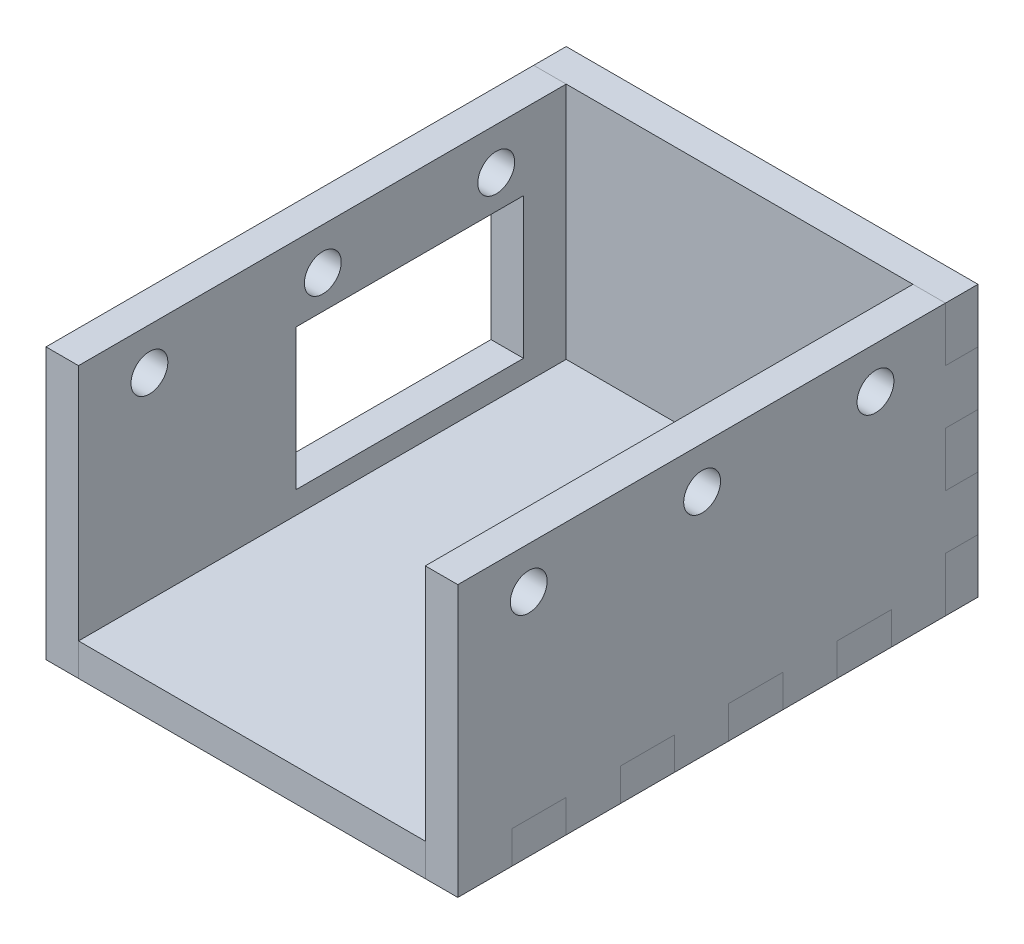
SolidWorks part; units mm, degrees
ref_plane "Front Plane" through (0, 0, 0) normal (0, 0, 1) x (1, 0, 0)
ref_plane "Top Plane" through (0, 0, 0) normal (0, 1, 0) x (1, 0, 0)
ref_plane "Right Plane" through (0, 0, 0) normal (1, 0, 0) x (0, 0, -1)
sketch "Sketch1" plane through (0, 0, 0) normal (0, 1, 0) x (1, 0, 0)
  line L33 (0, 0) -> (5, 0)
  line L34 (5, 0) -> (5, 3)
  line L54 (5, 3) -> (10, 3)
  line L55 (10, 3) -> (10, 0)
  line L56 (10, 0) -> (15, 0)
  line L57 (15, 0) -> (15, 3)
  line L58 (15, 3) -> (20, 3)
  line L59 (20, 3) -> (20, 0)
  line L60 (20, 0) -> (25, 0)
  line L61 (25, 0) -> (25, 3)
  line L62 (25, 3) -> (30, 3)
  line L63 (30, 3) -> (30, 0)
  line L64 (30, 0) -> (32, 0)
  line L65 (32, 0) -> (32, -5)
  line L66 (32, -5) -> (35, -5)
  line L67 (35, -5) -> (35, -10)
  line L68 (35, -10) -> (32, -10)
  line L69 (32, -10) -> (32, -15)
  line L70 (32, -15) -> (35, -15)
  line L71 (35, -15) -> (35, -20)
  line L72 (35, -20) -> (32, -20)
  line L73 (32, -20) -> (32, -25)
  line L74 (32, -25) -> (35, -25)
  line L75 (35, -25) -> (35, -30)
  line L76 (35, -30) -> (32, -30)
  line L77 (32, -30) -> (32, -35)
  line L78 (32, -35) -> (35, -35)
  line L79 (35, -35) -> (35, -40)
  line L80 (35, -40) -> (32, -40)
  line L81 (32, -40) -> (32, -45)
  line L82 (16, -1020.6314) -> (16, 48979.3686) construction
  line L83 (0, -40) -> (0, -45)
  line L84 (-3, -40) -> (0, -40)
  line L85 (-3, -35) -> (-3, -40)
  line L86 (0, -35) -> (-3, -35)
  line L87 (0, -30) -> (0, -35)
  line L88 (-3, -30) -> (0, -30)
  line L89 (-3, -25) -> (-3, -30)
  line L90 (0, -25) -> (-3, -25)
  line L91 (0, -20) -> (0, -25)
  line L92 (-3, -20) -> (0, -20)
  line L93 (-3, -15) -> (-3, -20)
  line L94 (0, -15) -> (-3, -15)
  line L95 (0, -10) -> (0, -15)
  line L96 (-3, -10) -> (0, -10)
  line L97 (-3, -5) -> (-3, -10)
  line L98 (0, -5) -> (-3, -5)
  line L99 (0, 0) -> (0, -5)
  line L100 (2, 0) -> (0, 0)
  line L101 (0, -45) -> (32, -45)
  point P21 (32, -2.5)
  dimension "D1" = 4
  dimension "D2" = 16
extrude "Boss-Extrude1" add sketch "Sketch1" along normal blind 3
sketch "Sketch4" plane through (32, 0, 0) normal (1, 0, 0) x (0, 0, -1)
  line L0 (-5, 3) -> (-5, 0)
  line L1 (-5, 0) -> (0, 0)
  line L2 (0, 0) -> (0, 3)
  line L3 (-5, 3) -> (-10, 3)
  line L4 (-15, 3) -> (-15, 0)
  line L5 (-15, 0) -> (-10, 0)
  line L6 (-10, 0) -> (-10, 3)
  line L7 (-15, 3) -> (-20, 3)
  line L8 (-25, 3) -> (-25, 0)
  line L9 (-25, 0) -> (-20, 0)
  line L10 (-20, 0) -> (-20, 3)
  line L11 (-25, 3) -> (-30, 3)
  line L12 (-35, 3) -> (-35, 0)
  line L13 (-35, 0) -> (-30, 0)
  line L14 (-30, 0) -> (-30, 3)
  line L15 (-35, 3) -> (-40, 3)
  line L16 (-40, 3) -> (-40, 0)
  line L17 (-40, 3) -> (-40, 0) construction
  line L18 (-40, 0) -> (-45, 0)
  line L19 (-45, 0) -> (-45, 3)
  line L20 (-45, 3) -> (-45, 25)
  line L21 (-45, 25) -> (0, 25)
  line L22 (0, 25) -> (0, 20)
  line L23 (0, 20) -> (3, 20)
  line L24 (3, 20) -> (3, 15)
  line L25 (3, 15) -> (0, 15)
  line L26 (0, 15) -> (0, 10)
  line L27 (0, 10) -> (3, 10)
  line L28 (3, 10) -> (3, 5)
  line L29 (3, 5) -> (0, 5)
  line L30 (0, 3) -> (0, 5)
  dimension "D1" = 22
extrude "Boss-Extrude2" add sketch "Sketch4" along normal blind 3 separate body
ref_plane "Plane1" through (16, 0, 0) normal (-1, 0, 0) x (0, 0, 1)
mirror "Mirror1" about plane through (16, 0, 0) normal (-1, 0, 0) of bodies 102
sketch "Sketch5" plane through (0, 0, 0) normal (0, 0, -1) x (-1, 0, 0)
  line L0 (-35, 25) -> (3, 25)
  line L1 (3, 25) -> (3, 20)
  line L2 (3, 20) -> (0, 20)
  line L3 (0, 20) -> (0, 15)
  line L4 (0, 15) -> (3, 15)
  line L5 (3, 15) -> (3, 10)
  line L6 (3, 10) -> (0, 10)
  line L7 (0, 10) -> (0, 5)
  line L8 (0, 5) -> (3, 5)
  line L9 (3, 5) -> (3, 0)
  line L10 (3, 0) -> (0, 0)
  line L11 (-5, 0) -> (-5, 3)
  line L12 (-5, 3) -> (-10, 3)
  line L13 (-10, 3) -> (-10, 0)
  line L14 (0, 0) -> (-5, 0)
  line L15 (-15, 0) -> (-15, 3)
  line L16 (-15, 3) -> (-20, 3)
  line L17 (-20, 3) -> (-20, 0)
  line L18 (-10, 0) -> (-15, 0)
  line L19 (-25, 0) -> (-25, 3)
  line L20 (-25, 3) -> (-30, 3)
  line L21 (-30, 3) -> (-30, 0)
  line L22 (-20, 0) -> (-25, 0)
  line L23 (-30, 0) -> (-32, 0)
  line L24 (-35, 0) -> (-35, 5)
  line L25 (-35, 5) -> (-32, 5)
  line L26 (-32, 5) -> (-32, 10)
  line L27 (-32, 10) -> (-35, 10)
  line L28 (-35, 10) -> (-35, 15)
  line L29 (-35, 15) -> (-32, 15)
  line L30 (-32, 15) -> (-32, 20)
  line L31 (-32, 20) -> (-35, 20)
  line L32 (-35, 20) -> (-35, 25)
  line L33 (-32, 0) -> (-35, 0)
  point P0 (-35, 0)
  point P27 (0, 0)
  dimension "D1" = 3
extrude "Boss-Extrude3" add sketch "Sketch5" along normal blind 3 separate body
sketch "Sketch6" plane through (-3, 0, 0) normal (-1, 0, 0) x (0, 0, 1)
  circle A0 centre (6.4572, 21.156) radius 1.7
  circle A1 centre (22.4572, 21.156) radius 1.7
  circle A2 centre (38.4572, 21.156) radius 1.7
  point P2 (3.3884, 17.5611)
  dimension "D1" = 3
extrude "Cut-Extrude1" cut sketch "Sketch6" against normal blind 44
sketch "Sketch8" plane through (-3, 0, 0) normal (-1, 0, 0) x (0, 0, 1)
  line L1 (3.9391, 5.0533) -> (24.9391, 5.0533)
  line L2 (3.9391, 5.0533) -> (3.9391, 18.0533)
  line L3 (3.9391, 18.0533) -> (24.9391, 18.0533)
  line L4 (24.9391, 5.0533) -> (24.9391, 18.0533)
  point P4 (3.9128, 5.1239)
  point P5 (3.9391, 5.0533)
  dimension "D1" = 13
  dimension "D2" = 21
extrude "Cut-Extrude2" cut sketch "Sketch8" against normal blind 5
equation "\"hardboard_thickness\"=3"
equation "\"D1@Boss-Extrude1\"=\"hardboard_thickness\""
equation "\"D1@Boss-Extrude2\"=\"hardboard_thickness\""
